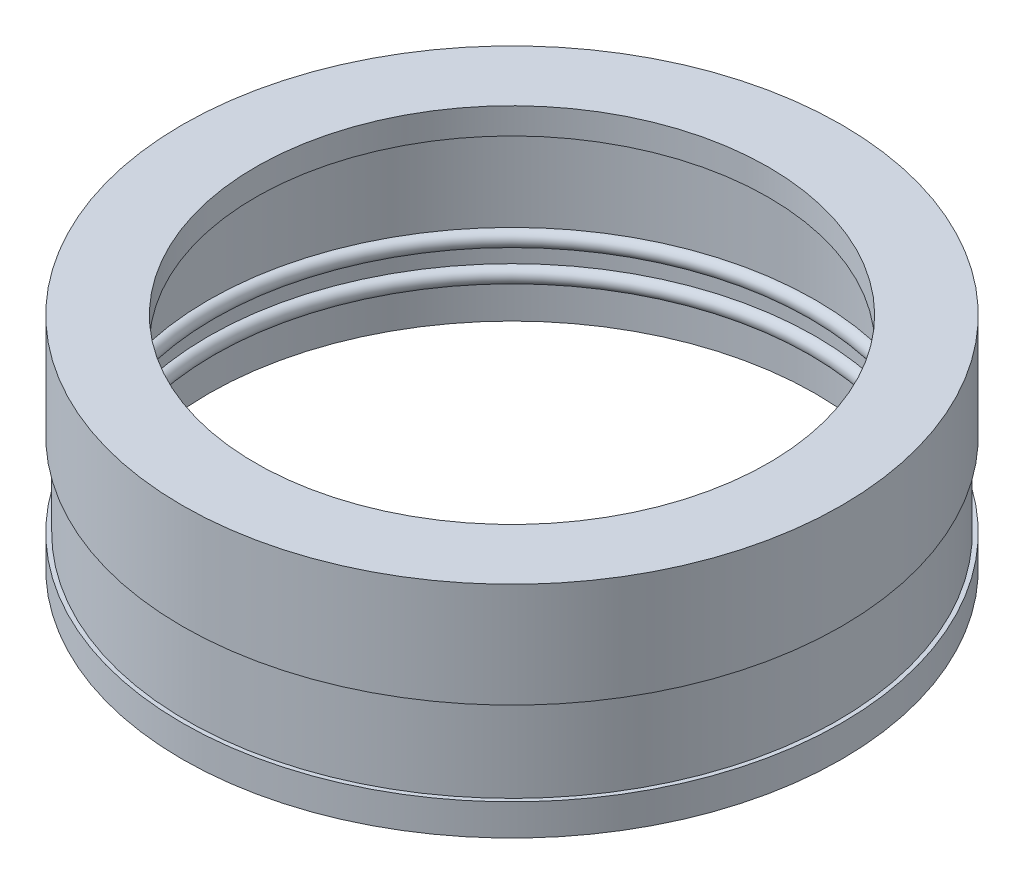
SolidWorks part; units mm, degrees
ref_plane "Front Plane" through (0, 0, 0) normal (0, 0, 1) x (1, 0, 0)
ref_plane "Top Plane" through (0, 0, 0) normal (0, 1, 0) x (1, 0, 0)
ref_plane "Right Plane" through (0, 0, 0) normal (1, 0, 0) x (0, 0, -1)
sketch "Sketch1" plane through (0, 0, 0) normal (0, 0, 1) x (1, 0, 0)
  line L0 (0, 0) -> (0, 11.5442) construction
  line L1 (0, 29.4) -> (0, 34.4) construction
  line L2 (49, 42) -> (63, 42)
  line L3 (63, 42) -> (63, 22)
  line L4 (63, 22) -> (62.2, 22)
  line L5 (62.2, 22) -> (62.2, 6)
  line L6 (62.2, 6) -> (63, 6)
  line L7 (63, 6) -> (63, 0)
  line L8 (63, 0) -> (58, 0)
  line L9 (58, 0) -> (58, 6.5)
  line L10 (58, 9.5) -> (58, 12.5)
  line L11 (58, 15.5) -> (58, 37)
  line L12 (58, 37) -> (49, 37)
  line L13 (49, 37) -> (49, 42)
  line L14 (18.6838, 34.4) -> (6.4684, 34.4) construction
  line L15 (18.6838, 29.4) -> (6.4684, 29.4) construction
  arc A0 (0, 34.4) -> (49, 42) centre (0, 196.1605) ccw construction
  arc A1 (0, 29.4) -> (49, 37) centre (0, 191.1605) ccw construction
  arc A2 (58, 12.5) -> (58, 15.5) centre (58, 14) cw
  arc A3 (58, 6.5) -> (58, 9.5) centre (58, 8) cw
  dimension "D8" = 1.5
  dimension "D1" = 126
  dimension "D2" = 14
  dimension "D3" = 42
  dimension "D4" = 20
  dimension "D5" = 6
  dimension "D6" = 0.8
  dimension "D7" = 5
  dimension "D9" = 6.5
  dimension "D10" = 3
  dimension "D11" = 7.6
revolve "Revolve1" add sketch "Sketch1" angle 360 about L0
